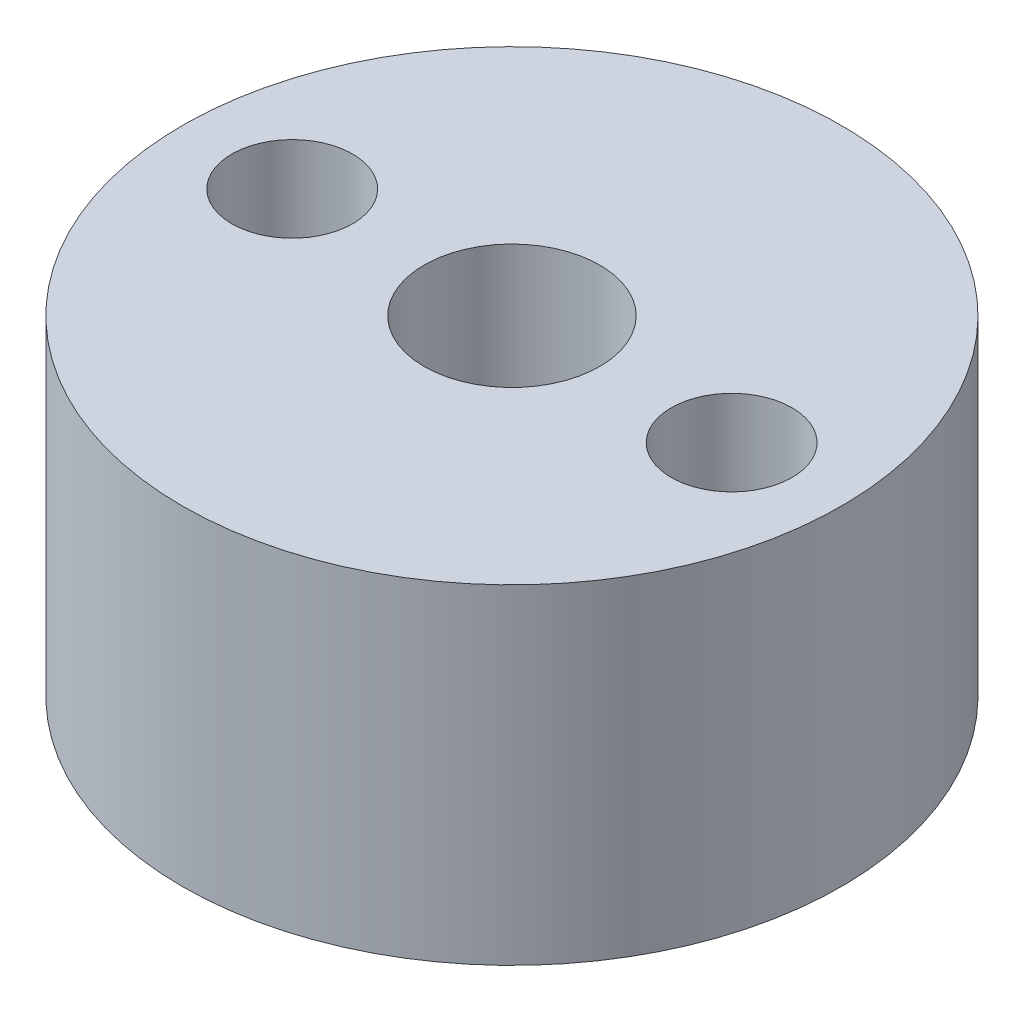
SolidWorks part; units mm, degrees
ref_plane "Front Plane" through (0, 0, 0) normal (0, 0, 1) x (1, 0, 0)
ref_plane "Top Plane" through (0, 0, 0) normal (0, 1, 0) x (1, 0, 0)
ref_plane "Right Plane" through (0, 0, 0) normal (1, 0, 0) x (0, 0, -1)
sketch "Sketch1" plane through (0, 0, 0) normal (0, 1, 0) x (1, 0, 0)
  line L0 (0, 15) -> (0, -15) construction
  circle A0 centre (0, 0) radius 4
  circle A1 centre (0, 0) radius 15
  circle A2 centre (-10, 0) radius 2.75
  circle A3 centre (10, 0) radius 2.75
  dimension "D1" = 10
  dimension "D2" = 8
  dimension "D3" = 30
  dimension "D4" = 5.5
extrude "Boss-Extrude1" add sketch "Sketch1" along normal blind 15
